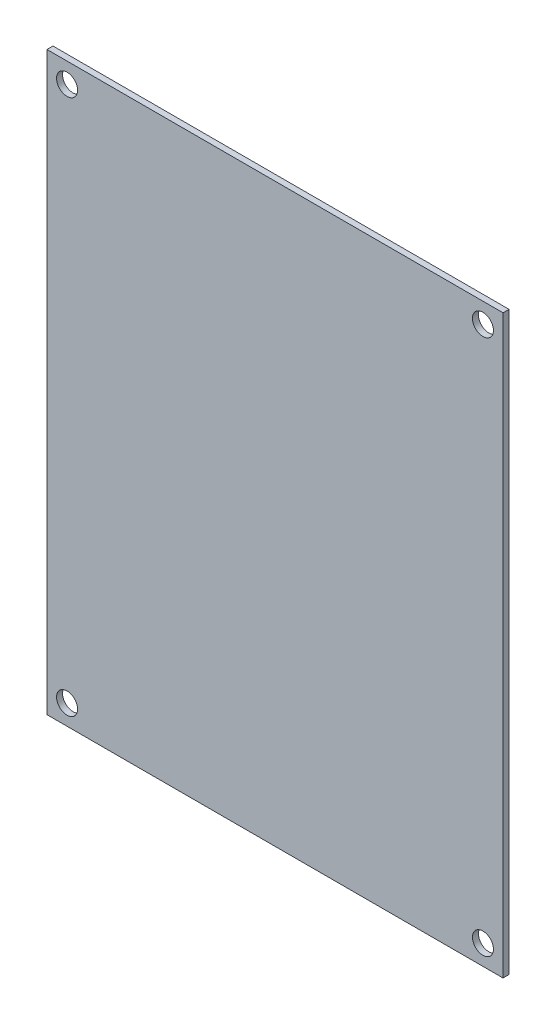
SolidWorks part; units mm, degrees
ref_plane "Front Plane" through (0, 0, 0) normal (0, 0, 1) x (1, 0, 0)
ref_plane "Top Plane" through (0, 0, 0) normal (0, 1, 0) x (1, 0, 0)
ref_plane "Right Plane" through (0, 0, 0) normal (1, 0, 0) x (0, 0, -1)
sketch "Sketch1" plane through (0, 0, 0) normal (0, 0, 1) x (1, 0, 0)
  line L0 (-34.65, 44.65) -> (-34.65, -44.65) construction
  line L1 (-38, 48) -> (38, 48)
  line L2 (-38, 48) -> (-38, -48)
  line L3 (-38, -48) -> (38, -48)
  line L4 (38, 48) -> (38, -48)
  line L5 (-38, 48) -> (38, -48) construction
  line L6 (-38, -48) -> (38, 48) construction
  line L7 (-34.65, -44.65) -> (34.65, -44.65) construction
  line L8 (34.65, -44.65) -> (34.65, 44.65) construction
  line L9 (34.65, 44.65) -> (-34.65, 44.65) construction
  line L10 (0, 44.65) -> (0, -44.65) construction
  circle A0 centre (-34.65, 44.65) radius 1.75
  circle A1 centre (34.65, 44.65) radius 1.75
  circle A2 centre (34.65, -44.65) radius 1.75
  circle A3 centre (-34.65, -44.65) radius 1.75
  point P0 (0, 0)
  point P17 (0, 0)
  dimension "D1" = 3.5
  dimension "D2" = 76
  dimension "D3" = 96
  dimension "D4" = 3.35
  dimension "D5" = 3.35
extrude "Boss-Extrude1" add sketch "Sketch1" along normal blind 1
